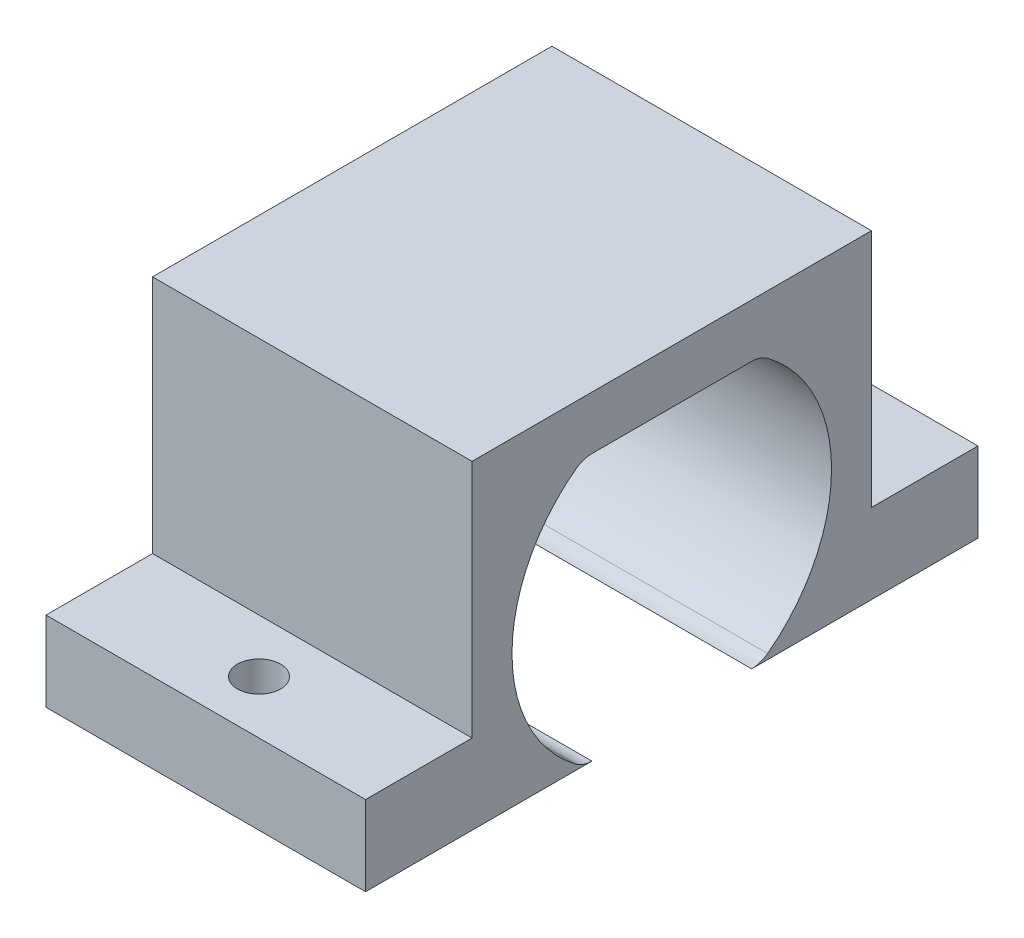
SolidWorks part; units mm, degrees
material "PLA"
ref_plane "Alzado" through (0, 0, 0) normal (0, 0, 1) x (1, 0, 0)
ref_plane "Planta" through (0, 0, 0) normal (0, 1, 0) x (1, 0, 0)
ref_plane "Vista lateral" through (0, 0, 0) normal (1, 0, 0) x (0, 0, -1)
sketch "Croquis1" plane through (0, 0, 0) normal (1, 0, 0) x (0, 0, -1)
  line L0 (-2.8586, -6) -> (2.8586, -6)
  line L1 (-7.5, -6) -> (7.5, -6)
  line L2 (-7.5, -6) -> (-7.5, 6)
  line L3 (-7.5, 6) -> (7.5, 6)
  line L4 (7.5, -6) -> (7.5, 6)
  line L5 (-7.5, -6) -> (7.5, 6) construction
  line L6 (-7.5, 6) -> (7.5, -6) construction
  line L7 (7.5, -6) -> (11.5, -6)
  line L8 (7.5, -6) -> (7.5, -3)
  line L9 (7.5, -3) -> (11.5, -3)
  line L10 (11.5, -6) -> (11.5, -3)
  line L11 (-7.5, -6) -> (-11.5, -6)
  line L12 (-7.5, -6) -> (-7.5, -3)
  line L13 (-7.5, -3) -> (-11.5, -3)
  line L14 (-11.5, -6) -> (-11.5, -3)
  line L16 (0, 4) -> (0, 5.0669) construction
  point P0 (0, 0)
  dimension "D8" = 7.5
  dimension "D1" = 15
  dimension "D2" = 12
  dimension "D3" = 3
  dimension "D4" = 3
  dimension "D5" = 4
  dimension "D6" = 4
extrude "Saliente-Extruir1" add sketch "Croquis1" along normal blind 12 contours L14 L11 L2 L13 | L1 L4 L3 L2 | L7 L10 L9 L4
sketch "Croquis4" plane through (12, 0, 0) normal (1, 0, 0) x (0, 0, -1)
  line L0 (-3, -6) -> (3, -6)
  line L1 (3, 4) -> (-3, 4)
  line L2 (0, -1) -> (0, 2.3958) construction
  arc A5 (3.6, -5.8) -> (3.6, 3.8) centre (0, -1) ccw
  arc A6 (3.6, 3.8) -> (3, 4) centre (3, 3) ccw
  arc A7 (-3, -6) -> (-3.6, -5.8) centre (-3, -5) cw
  arc A8 (-3.6, -5.8) -> (-3.6, 3.8) centre (0, -1) cw
  arc A10 (3, -6) -> (3.6, -5.8) centre (3, -5) ccw
  arc A11 (-3.6, 3.8) -> (-3, 4) centre (-3, 3) cw
  point P18 (0, 4)
extrude "Cortar-Extruir2" cut sketch "Croquis4" against normal blind 12
sketch "Croquis5" plane through (0, -3, 0) normal (0, 1, 0) x (1, 0, 0)
  line L0 (12, 11.5) -> (0, 11.5) construction
  line L2 (0, 7.5) -> (0, 11.5) construction
  line L4 (0, 0) -> (16.4644, 0) construction
  circle A1 centre (6, 9.5) radius 0.81
  circle A2 centre (6, -9.5) radius 0.81
  dimension "D1" = 2
  dimension "D3" = 6
  dimension "D2" = 1.62
  dimension "D4" = 19
extrude "Cortar-Extruir3" cut sketch "Croquis5" against normal blind 3
